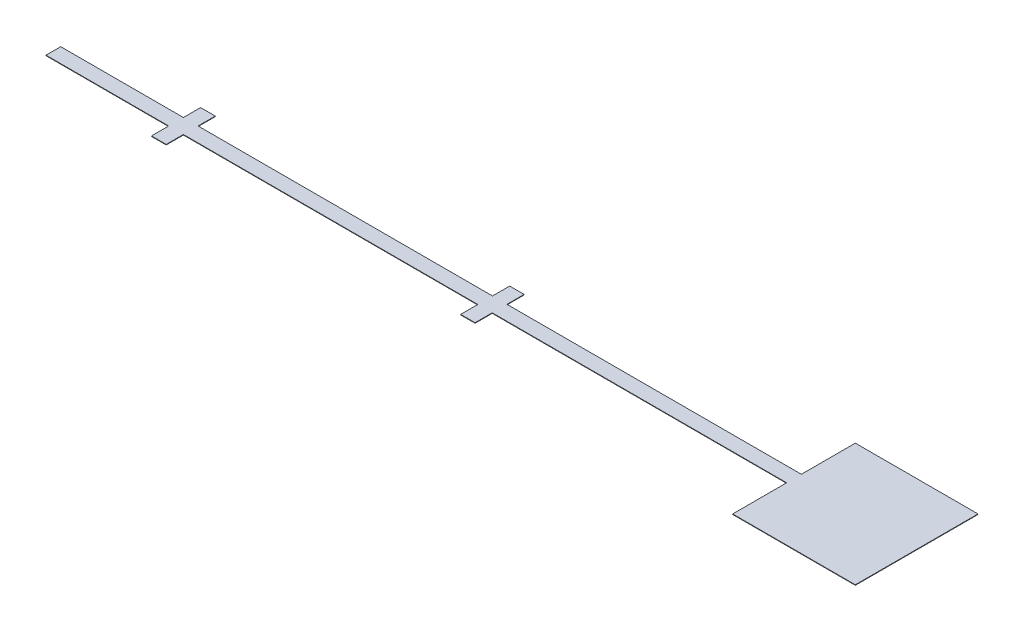
SolidWorks part; units mm, degrees
ref_plane "Front Plane" through (0, 0, 0) normal (0, 0, 1) x (1, 0, 0)
ref_plane "Top Plane" through (0, 0, 0) normal (0, 1, 0) x (1, 0, 0)
ref_plane "Right Plane" through (0, 0, 0) normal (1, 0, 0) x (0, 0, -1)
sketch "Sketch1" plane through (0, 0, 0) normal (0, 1, 0) x (1, 0, 0)
  line L0 (-224.4444, 42.7778) -> (-224.4444, 12.7778)
  line L1 (-224.4444, 12.7778) -> (25.5556, 12.7778)
  line L2 (25.5556, 12.7778) -> (25.5556, -22.2222)
  line L3 (25.5556, -22.2222) -> (55.5556, -22.2222)
  line L4 (55.5556, -22.2222) -> (55.5556, 12.7778)
  line L5 (55.5556, 12.7778) -> (655.5556, 12.7778)
  line L6 (655.5556, 12.7778) -> (655.5556, -22.2222)
  line L7 (655.5556, -22.2222) -> (685, -22.2222)
  line L8 (685, -22.2222) -> (685, 12.7778)
  line L9 (685, 12.7778) -> (1285, 12.7778)
  line L10 (1285, 12.7778) -> (1285, -97.2222)
  line L11 (1285, -97.2222) -> (1535, -97.2222)
  line L12 (1535, -97.2222) -> (1535, 152.7778)
  line L13 (1535, 152.7778) -> (1285, 152.7778)
  line L14 (1285, 152.7778) -> (1285, 42.7778)
  line L15 (1285, 42.7778) -> (685, 42.7778)
  line L16 (685, 42.7778) -> (685, 77.7778)
  line L17 (685, 77.7778) -> (655.5556, 77.7778)
  line L18 (655.5556, 77.7778) -> (655.5556, 42.7778)
  line L19 (655.5556, 42.7778) -> (55.5556, 42.7778)
  line L20 (55.5556, 42.7778) -> (55.5556, 77.7778)
  line L21 (55.5556, 77.7778) -> (25.5556, 77.7778)
  line L22 (25.5556, 77.7778) -> (25.5556, 42.7778)
  line L23 (25.5556, 42.7778) -> (-224.4444, 42.7778)
  dimension "D1" = 30
  dimension "D2" = 250
  dimension "D3" = 30
  dimension "D4" = 30
  dimension "D5" = 35
  dimension "D6" = 35
  dimension "D7" = 100
  dimension "D8" = 30
  dimension "D9" = 100
  dimension "D10" = 30
  dimension "D11" = 35
  dimension "D12" = 35
  dimension "D13" = 600
  dimension "D14" = 600
  dimension "D15" = 250
  dimension "D16" = 250
  dimension "D17" = 110
extrude "Boss-Extrude1" add sketch "Sketch1" along normal blind 1
